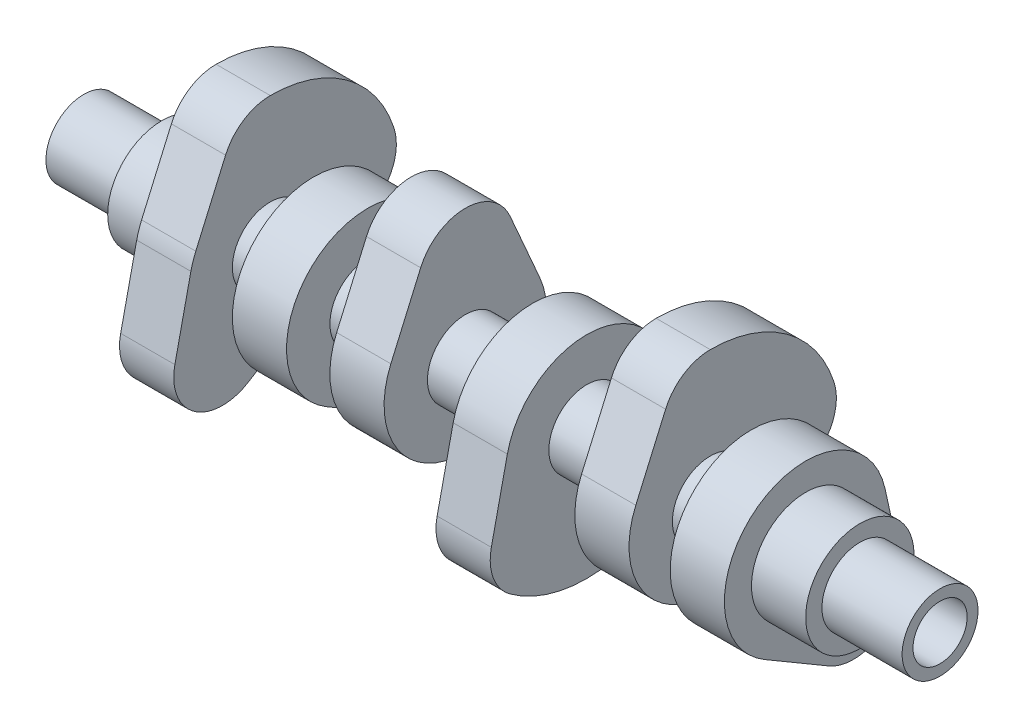
SolidWorks part; units mm, degrees
ref_plane "Front Plane" through (0, 0, 0) normal (0, 0, 1) x (1, 0, 0)
ref_plane "Top Plane" through (0, 0, 0) normal (0, 1, 0) x (1, 0, 0)
ref_plane "Right Plane" through (0, 0, 0) normal (1, 0, 0) x (0, 0, -1)
sketch "Sketch1" plane through (0, 0, 0) normal (1, 0, 0) x (0, 0, -1)
  line L0 (-5.2379, 11.811) -> (-8.7298, 3.81)
  line L2 (12.8515, -1.3317) -> (6.3212, -7.1252)
  line L3 (-2.6209, -12.5838) -> (6.3212, -7.1252)
  line L4 (-11.1799, -6.4765) -> (-9.302, 2.0489)
  arc A0 (-8.7298, 3.81) -> (-9.302, 2.0489) centre (0, 0) ccw
  arc A1 (0, 15.24) -> (-5.2379, 11.811) centre (0, 9.525) ccw
  arc A2 (12.8515, -1.3317) -> (14.4941, 4.7094) centre (9.0588, 2.9434) ccw
  arc A3 (-11.1799, -6.4765) -> (-2.6209, -12.5838) centre (-5.5987, -7.7059) ccw
  arc A4 (14.4941, 4.7094) -> (0, 15.24) centre (0, 0) ccw
  arc A5 (3.4484, -8.8789) -> (6.3212, -7.1252) centre (0, 0) ccw
  dimension "D1" = 11.43
  dimension "D2" = 19.05
  dimension "D3" = 11.43
  dimension "D4" = 11.43
  dimension "D5" = 72
  dimension "D6" = 144
extrude "Boss-Extrude1" add sketch "Sketch1" along normal blind 6.35 contours L2 A2 A4 A1 L0 A0 L4 A3 L3
sketch "Sketch2" plane through (6.35, 0, 0) normal (1, 0, 0) x (0, 0, -1)
  line L2 (11.1799, -6.4765) -> (9.302, 2.0489)
  line L3 (-4.8231, -8.2136) -> (2.7048, -12.6341)
  arc A2 (9.302, 2.0489) -> (-4.8231, -8.2136) centre (0, 0) ccw
  arc A3 (2.7048, -12.6341) -> (11.1799, -6.4765) centre (5.5987, -7.7059) ccw
  point P4 (0, 9.525)
  dimension "D1" = 19.05
  dimension "D2" = 11.43
  dimension "D3" = 144
extrude "Boss-Extrude2" add sketch "Sketch2" along normal blind 6.35 from offset 5.08 separate body
sketch "Sketch3" plane through (17.78, 0, 0) normal (1, 0, 0) x (0, 0, -1)
  line L2 (-5.2379, 11.811) -> (-8.7298, 3.81)
  line L3 (5.2379, 11.811) -> (8.7298, 3.81)
  arc A3 (-8.7298, 3.81) -> (8.7298, 3.81) centre (0, 0) ccw
  arc A4 (5.2379, 11.811) -> (-5.2379, 11.811) centre (0, 9.525) ccw
  dimension "D1" = 11.43
  dimension "D2" = 19.05
extrude "Boss-Extrude3" add sketch "Sketch3" along normal blind 6.35 from offset 5.08 separate body
sketch "Sketch4" plane through (29.21, 0, 0) normal (1, 0, 0) x (0, 0, -1)
  line L4 (-11.1799, -6.4765) -> (-9.302, 2.0489)
  line L8 (-11.1799, -6.4765) -> (-9.302, 2.0489) construction
  line L9 (9.302, 2.0489) -> (11.1799, -6.4765)
  arc A25 (8.9578, -12.3294) -> (11.1799, -6.4765) centre (5.5987, -7.7059) ccw
  arc A26 (-11.1799, -6.4765) -> (-8.9578, -12.3294) centre (-5.5987, -7.7059) ccw
  arc A27 (-8.9578, -12.3294) -> (8.9578, -12.3294) centre (0, 0) ccw
  arc A29 (9.302, 2.0489) -> (-9.302, 2.0489) centre (0, 0) ccw
  point P6 (0, 9.525)
  dimension "D2" = 11.43
  dimension "D5" = 72
  dimension "D3" = 11.43
  dimension "D4" = 144
extrude "Boss-Extrude4" add sketch "Sketch4" along normal blind 6.35 from offset 7.874 separate body
sketch "Sketch5" plane through (53.34, 0, 0) normal (1, 0, 0) x (0, 0, -1)
  line L3 (-5.2379, 11.811) -> (-8.7298, 3.81)
  line L4 (12.8515, -1.3317) -> (6.3212, -7.1252)
  arc A19 (-8.7298, 3.81) -> (6.3212, -7.1252) centre (0, 0) ccw
  arc A21 (12.8515, -1.3317) -> (14.4941, 4.7094) centre (9.0588, 2.9434) ccw
  arc A22 (14.4941, 4.7094) -> (0, 15.24) centre (0, 0) ccw
  arc A23 (0, 15.24) -> (-5.2379, 11.811) centre (0, 9.525) ccw
  dimension "D2" = 11.43
  dimension "D3" = 72
  dimension "D4" = 30.48
extrude "Boss-Extrude5" add sketch "Sketch5" along normal blind 6.35 from offset 1.778 separate body offset against normal yes
sketch "Sketch6" plane through (57.912, 0, 0) normal (1, 0, 0) x (0, 0, -1)
  line L6 (11.1799, -6.4765) -> (9.302, 2.0489)
  line L7 (2.7048, -12.6341) -> (-4.8231, -8.2136)
  arc A18 (9.302, 2.0489) -> (-4.8231, -8.2136) centre (0, 0) ccw
  arc A19 (2.7048, -12.6341) -> (11.1799, -6.4765) centre (5.5987, -7.7059) ccw
  point P4 (0, 9.525)
  dimension "D1" = 144
  dimension "D3" = 11.43
  dimension "D2" = 19.05
extrude "Boss-Extrude6" add sketch "Sketch6" along normal blind 6.35 from offset 4.826 separate body
sketch "Sketch7" plane through (83.82, 0, 0) normal (1, 0, 0) x (0, 0, -1)
  circle A0 centre (0, 0) radius 4.445
  dimension "D1" = 8.89
extrude "Boss-Extrude7" add sketch "Sketch7" against normal blind 100.33 from offset 1.016 separate body
sketch "Sketch8" plane through (84.836, 0, 0) normal (1, 0, 0) x (0, 0, -1)
  circle A0 centre (0, 0) radius 3.175
  dimension "D1" = 6.35
extrude "Cut-Extrude1" cut sketch "Sketch8" against normal through all both and the other way through all
sketch "Sketch9" plane through (69.088, 0, 0) normal (1, 0, 0) x (0, 0, -1)
  circle A0 centre (0, 0) radius 6.35
  dimension "D1" = 12.7
extrude "Boss-Extrude8" add sketch "Sketch9" along normal blind 6.35
sketch "Sketch10" plane through (0, 0, 0) normal (-1, 0, 0) x (0, 0, 1)
  circle A0 centre (0, 0) radius 6.35
  dimension "D1" = 12.7
extrude "Boss-Extrude9" add sketch "Sketch10" along normal blind 6.35
